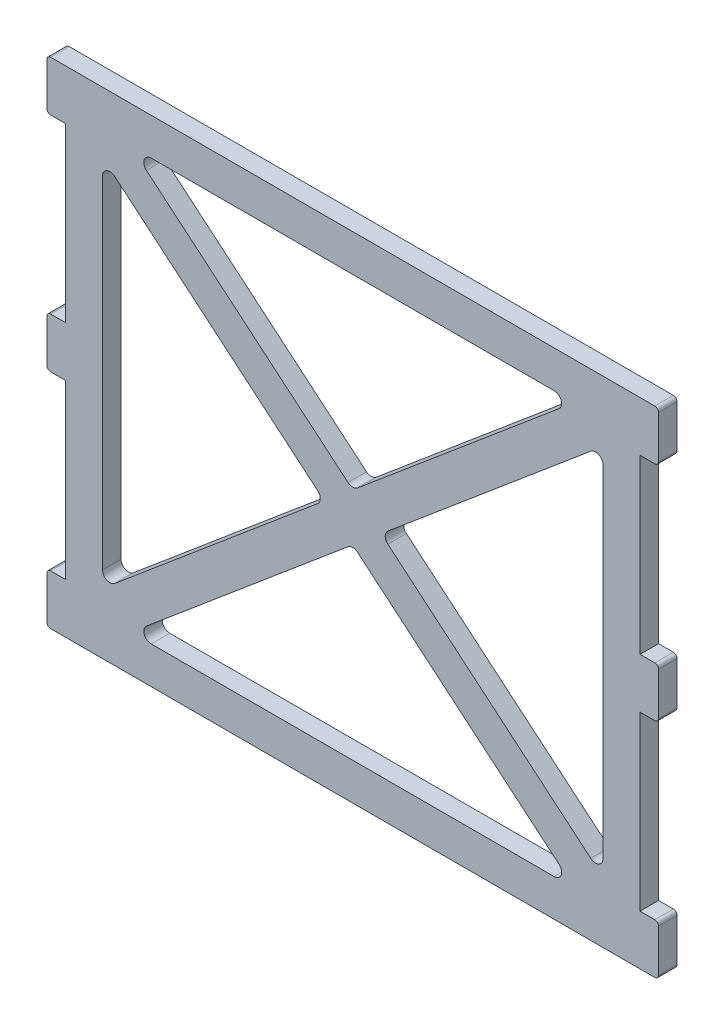
SolidWorks part; units mm, degrees
ref_plane "Front Plane" through (0, 0, 0) normal (0, 0, 1) x (1, 0, 0)
ref_plane "Top Plane" through (0, 0, 0) normal (0, 1, 0) x (1, 0, 0)
ref_plane "Right Plane" through (0, 0, 0) normal (1, 0, 0) x (0, 0, -1)
sketch "Sketch2" plane through (0, 0, 0) normal (0, 0, 1) x (1, 0, 0)
  line L0 (-98.425, 84.7725) -> (-98.425, 67.6275)
  line L1 (-98.425, 84.7725) -> (98.425, 84.7725)
  line L2 (-98.425, 84.7725) -> (-98.425, -84.7725)
  line L3 (-98.425, -84.7725) -> (98.425, -84.7725)
  line L4 (98.425, 84.7725) -> (98.425, -84.7725)
  line L5 (-98.425, 84.7725) -> (-104.775, 84.7725)
  line L6 (-98.425, 84.7725) -> (-98.425, 67.6275)
  line L7 (-98.425, 67.6275) -> (-104.775, 67.6275)
  line L8 (-104.775, 84.7725) -> (-104.775, 67.6275)
  line L9 (-98.425, 8.5725) -> (-104.775, 8.5725)
  line L10 (-104.775, 8.5725) -> (-104.775, -8.5725)
  line L11 (-98.425, -8.5725) -> (-104.775, -8.5725)
  line L12 (-98.425, 8.5725) -> (-98.425, -8.5725)
  line L13 (-98.425, -67.6275) -> (-104.775, -67.6275)
  line L14 (-104.775, -67.6275) -> (-104.775, -84.7725)
  line L15 (-98.425, -84.7725) -> (-104.775, -84.7725)
  line L16 (-98.425, -67.6275) -> (-98.425, -84.7725)
  line L17 (104.775, 8.5725) -> (98.425, 8.5725)
  line L18 (98.425, 8.5725) -> (98.425, -8.5725)
  line L19 (104.775, -8.5725) -> (98.425, -8.5725)
  line L20 (104.775, 8.5725) -> (104.775, -8.5725)
  line L21 (104.775, -67.6275) -> (98.425, -67.6275)
  line L22 (98.425, -67.6275) -> (98.425, -84.7725)
  line L23 (104.775, -84.7725) -> (98.425, -84.7725)
  line L24 (104.775, -67.6275) -> (104.775, -84.7725)
  line L25 (104.775, 84.7725) -> (98.425, 84.7725)
  line L26 (98.425, 84.7725) -> (98.425, 67.6275)
  line L27 (104.775, 67.6275) -> (98.425, 67.6275)
  line L28 (104.775, 84.7725) -> (104.775, 67.6275)
  line L29 (-98.425, 84.7725) -> (-98.425, 8.5725) construction
  line L30 (-98.425, 84.7725) -> (104.775, 84.7725) construction
  point P4 (0, 84.7725)
  point P6 (-98.425, 0)
  dimension "D1" = 169.545
  dimension "D2" = 196.85
  dimension "D3" = 17.145
  dimension "D4" = 6.35
  dimension "D7" = 76.2
  dimension "D8" = 203.2
  dimension "D5" = 3
  dimension "D6" = 2
extrude "Boss-Extrude1" add sketch "Sketch2" along normal blind 6.35 contours L4 L1 L0 L2 L3 | L5 L8 L7 L0 | L11 L2 L9 L10 | L28 L25 L4 L27 | L20 L17 L4 L19 | L24 L21 L4 L23 | L14 L15 L16 L13
sketch "Sketch3" plane through (0, 0, 6.35) normal (0, 0, 1) x (1, 0, 0)
  line L0 (-104.775, 84.7725) -> (104.775, 84.7725) construction
  line L1 (-85.725, 72.0725) -> (85.725, 72.0725)
  line L2 (-85.725, 72.0725) -> (-85.725, -72.0725)
  line L3 (-85.725, -72.0725) -> (85.725, -72.0725)
  line L4 (85.725, 72.0725) -> (85.725, -72.0725)
  line L5 (-98.425, 67.6275) -> (-98.425, 8.5725) construction
  line L6 (98.425, 67.6275) -> (98.425, 8.5725) construction
  line L7 (-104.775, -84.7725) -> (104.775, -84.7725) construction
  line L8 (-85.725, 72.0725) -> (85.725, -72.0725)
  line L9 (85.725, 72.0725) -> (-85.725, -72.0725)
  line L10 (-80.8645, 76.1589) -> (90.5855, -67.9861)
  line L11 (-90.5855, 67.9861) -> (80.8645, -76.1589)
  line L12 (-85.725, 72.0725) -> (-90.5855, 67.9861) construction
  line L13 (-85.725, 72.0725) -> (-80.8645, 76.1589) construction
  line L14 (90.5855, 67.9861) -> (-80.8645, -76.1589)
  line L15 (85.725, 72.0725) -> (90.5855, 67.9861) construction
  line L16 (80.8645, 76.1589) -> (-90.5855, -67.9861)
  line L17 (85.725, 72.0725) -> (80.8645, 76.1589) construction
  point P12 (76.0041, 72.0725)
  point P25 (-85.725, 63.8997)
  point P29 (-85.725, 63.8997)
  point P30 (-85.725, 63.8997)
  point P31 (-85.725, 63.8997)
  point P32 (-76.0041, 72.0725)
  point P33 (85.725, -63.8997)
  point P34 (85.725, 63.8997)
  point P35 (76.0041, -72.0725)
  point P36 (-76.0041, -72.0725)
  point P37 (-85.725, -63.8997)
  dimension "D1" = 12.7
  dimension "D2" = 12.7
  dimension "D3" = 12.7
  dimension "D4" = 12.7
  dimension "D6" = 6.35
  dimension "D8" = 6.35
  dimension "D10" = 6.35
  dimension "D12" = 6.35
  dimension "D7" = 2
  dimension "D5" = 2
  dimension "D9" = 2
  dimension "D11" = 2
extrude "Cut-Extrude1" cut sketch "Sketch3" against normal through all contours L16 L11 L2 | L16 L1 L10 | L4 L14 L10 | L11 L14 L3
fillet "Fillet1" radius 2.54 12 edges at (-85.725, 63.8997, 3.175) (-9.7209, 0, 3.175) (-85.725, -63.8997, 3.175) (-76.0041, -72.0725, 3.175) (0, -8.1728, 3.175) (76.0041, -72.0725, 3.175) (85.725, -63.8997, 3.175) (9.7209, 0, 3.175) (85.725, 63.8997, 3.175) (76.0041, 72.0725, 3.175) (0, 8.1728, 3.175) (-76.0041, 72.0725, 3.175)
fillet "Fillet2" radius 1.27 12 edges at (104.775, 67.6275, 3.175) (104.775, 84.7725, 3.175) (104.775, -8.5725, 3.175) (104.775, 8.5725, 3.175) (104.775, -84.7725, 3.175) (104.775, -67.6275, 3.175) (-104.775, -84.7725, 3.175) (-104.775, -67.6275, 3.175) (-104.775, -8.5725, 3.175) (-104.775, 8.5725, 3.175) (-104.775, 67.6275, 3.175) (-104.775, 84.7725, 3.175)
